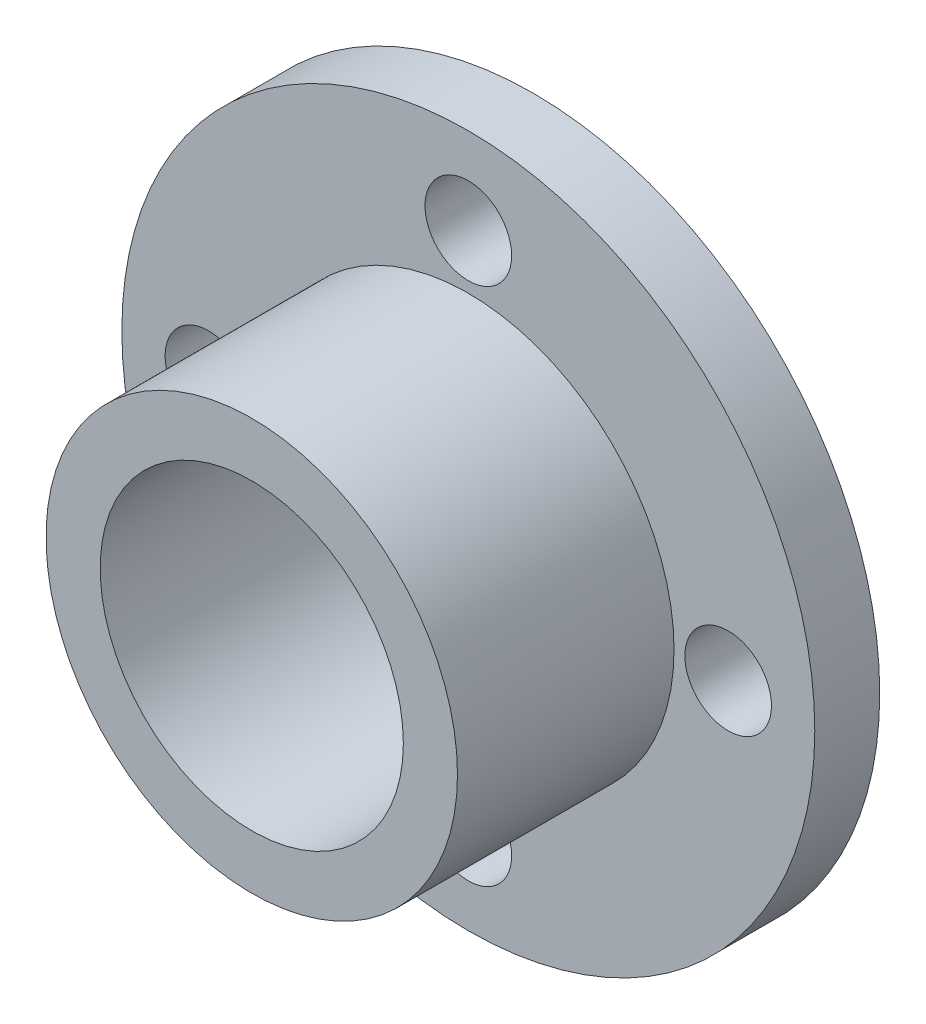
SolidWorks part; units mm, degrees
ref_plane "前视基准面" through (0, 0, 0) normal (0, 0, 1) x (1, 0, 0)
ref_plane "上视基准面" through (0, 0, 0) normal (0, 1, 0) x (1, 0, 0)
ref_plane "右视基准面" through (0, 0, 0) normal (1, 0, 0) x (0, 0, -1)
sketch "草图1" plane through (0, 0, 0) normal (0, 0, 1) x (1, 0, 0)
  circle A0 centre (0, 0) radius 16
  circle A1 centre (0, 0) radius 7
  dimension "D1" = 14
  dimension "D2" = 32
extrude "凸台-拉伸1" add sketch "草图1" along normal blind 3
sketch "草图2" plane through (0, 0, 3) normal (0, 0, 1) x (1, 0, 0)
  circle A0 centre (0, 0) radius 7
  circle A1 centre (0, 0) radius 9.5
  dimension "D1" = 19
  dimension "D2" = 14
extrude "凸台-拉伸2" add sketch "草图2" along normal blind 10
sketch "草图3" plane through (0, 0, 3) normal (0, 0, 1) x (1, 0, 0)
  circle A0 centre (0, 0) radius 12 construction
  circle A1 centre (0, -12) radius 2
  circle A2 centre (-12, 0) radius 2
  circle A3 centre (0, 12) radius 2
  circle A4 centre (12, 0) radius 2
  dimension "D1" = 24
  dimension "D2" = 4
  dimension "D3" = 4
extrude "切除-拉伸1" cut sketch "草图3" against normal blind 10
